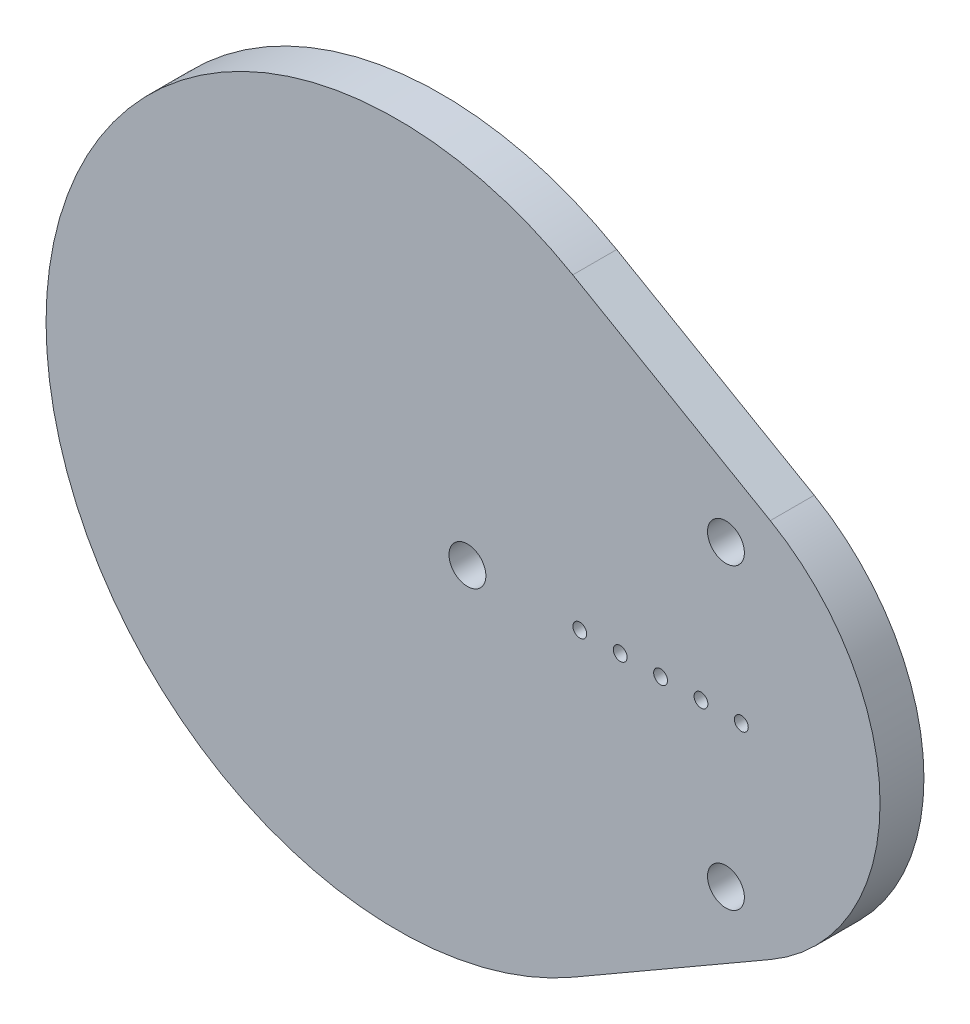
SolidWorks part; units mm, degrees
ref_plane "Front" through (0, 0, 0) normal (0, 0, 1) x (1, 0, 0)
ref_plane "Top" through (0, 0, 0) normal (0, 1, 0) x (1, 0, 0)
ref_plane "Right" through (0, 0, 0) normal (1, 0, 0) x (0, 0, -1)
sketch "Sketch1" plane through (0, 0, 0) normal (0, 0, 1) x (1, 0, 0)
  line L0 (31.75, 0) -> (31.75, -38.4943)
  line L1 (-5.842, 0) -> (-11.684, 0) construction
  line L2 (15.875, 27.4963) -> (-12.7, 43.9941)
  line L3 (15.875, -27.4963) -> (-12.7, -43.9941)
  line L4 (5.842, 0) -> (0, 0) construction
  line L5 (0, 0) -> (-5.842, 0) construction
  line L6 (5.842, 0) -> (11.684, 0) construction
  circle A0 centre (0, 0) radius 12.7 construction
  circle A1 centre (0, 0) radius 31.75
  circle A4 centre (-27.94, 0) radius 2.665
  circle A5 centre (9.455, 21.59) radius 2.665
  circle A6 centre (9.455, -21.59) radius 2.665
  circle A8 centre (0, 0) radius 1
  circle A9 centre (-5.842, 0) radius 1
  circle A10 centre (5.842, 0) radius 1
  circle A11 centre (-11.684, 0) radius 1
  circle A12 centre (11.684, 0) radius 1
  arc A13 (-12.7, 43.9941) -> (-12.7, -43.9941) centre (-38.1, 0) ccw
  point P17 (-3.01, 0)
  dimension "D1" = 25.4
  dimension "D2" = 63.5
  dimension "D3" = 27.94
  dimension "D5" = 5.33
  dimension "D7" = 2
  dimension "D8" = 5.842
  dimension "D9" = 21.59
  dimension "D10" = 43.18
  dimension "D6" = 3
extrude "Boss-Extrude1" add sketch "Sketch1" along normal blind 6.35
